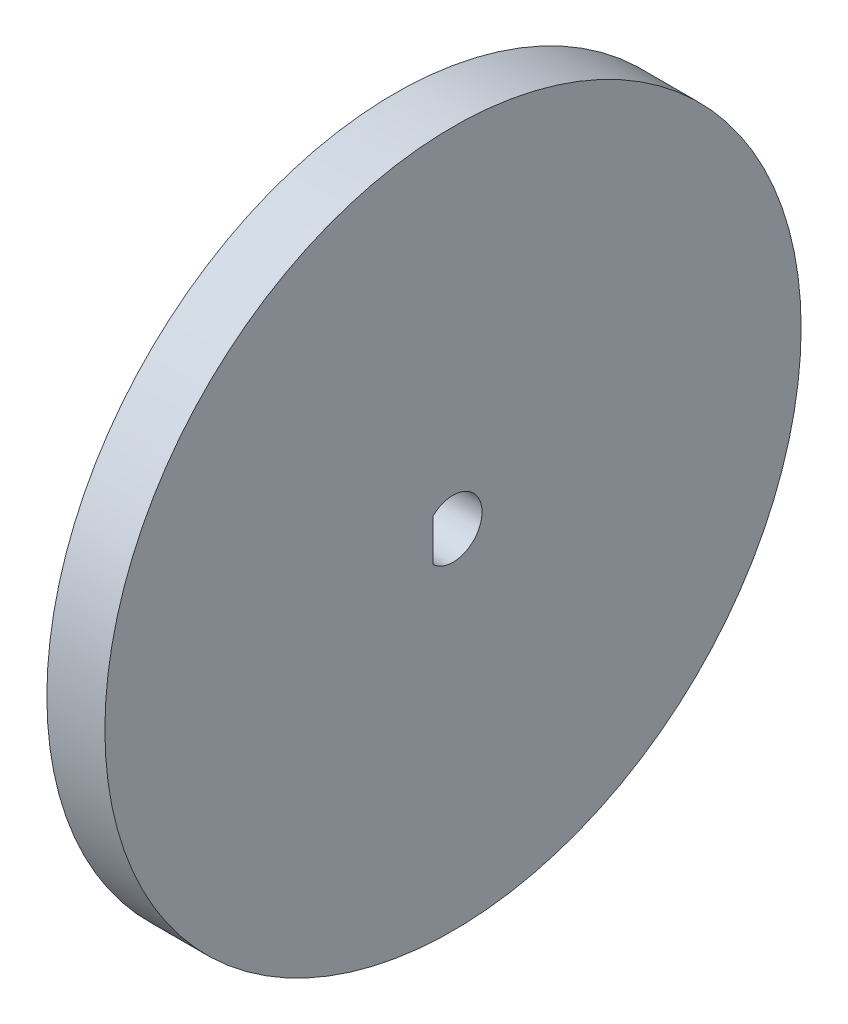
SolidWorks part; units mm, degrees
ref_plane "Front Plane" through (0, 0, 0) normal (0, 0, 1) x (1, 0, 0)
ref_plane "Top Plane" through (0, 0, 0) normal (0, 1, 0) x (1, 0, 0)
ref_plane "Right Plane" through (0, 0, 0) normal (1, 0, 0) x (0, 0, -1)
sketch "Sketch1" plane through (0, 0, 0) normal (1, 0, 0) x (0, 0, -1)
  line L0 (-2.1844, 2.3041) -> (-2.1844, -2.3041)
  line L1 (-2.1844, 0) -> (0, 0) construction
  circle A0 centre (0, 0) radius 38.1
  arc A1 (-2.1844, -2.3041) -> (-2.1844, 2.3041) centre (0, 0) ccw
  point P3 (3.175, 0)
  dimension "D1" = 76.2
  dimension "D2" = 6.35
  dimension "D3" = 5.3594
extrude "Boss-Extrude1" add sketch "Sketch1" along normal blind 6.35
